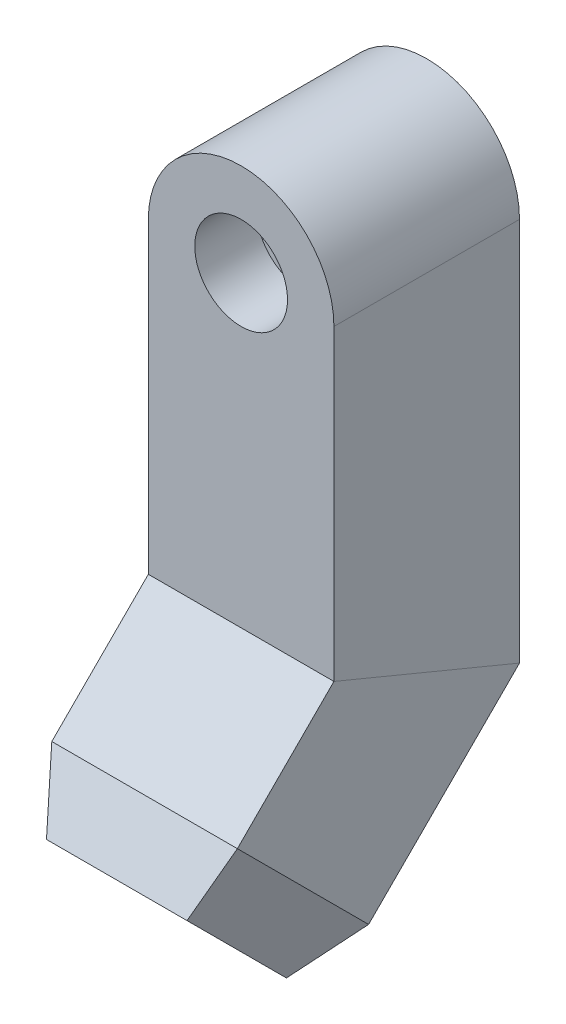
SolidWorks part; units mm, degrees
ref_plane "Front Plane" through (0, 0, 0) normal (0, 0, 1) x (1, 0, 0)
ref_plane "Top Plane" through (0, 0, 0) normal (0, 1, 0) x (1, 0, 0)
ref_plane "Right Plane" through (0, 0, 0) normal (1, 0, 0) x (0, 0, -1)
ref_plane "Plane2" through (0, 96.393, 0) normal (0, 1, 0) x (1, 0, 0)
sketch "Sketch10" plane through (0, 0, 0) normal (1, 0, 0) x (0, 0, -1)
  line L0 (0, 96.393) -> (0, 25.4)
  line L1 (55, 96.393) -> (-55, 96.393) construction
  line L2 (0, 25.4) -> (-25.4, 0)
  line L3 (55, 0) -> (-55, 0) construction
  dimension "D1" = 70.993
  dimension "D2" = 135
sketch "Sketch11" plane through (0, 96.393, 0) normal (0, 1, 0) x (1, 0, 0)
  line L1 (-19.05, -19.05) -> (19.05, -19.05)
  line L2 (-19.05, -19.05) -> (-19.05, 19.05)
  line L3 (-19.05, 19.05) -> (19.05, 19.05)
  line L4 (19.05, -19.05) -> (19.05, 19.05)
  line L5 (-19.05, -19.05) -> (19.05, 19.05) construction
  line L6 (-19.05, 19.05) -> (19.05, -19.05) construction
  point P0 (0, 0)
  dimension "D1" = 38.1
sweep "Sweep1" add profiles "Sketch11" path "Sketch10"
sketch "Sketch12" plane through (0, -12.7, 12.7) normal (0, -0.7071, 0.7071) x (1, 0, 0)
  line L8 (19.05, -1.0895) -> (19.05, 37.0105)
  line L9 (19.05, 37.0105) -> (-19.05, 37.0105)
  line L10 (-19.05, 37.0105) -> (-19.05, -1.0895)
  line L11 (-19.05, -1.0895) -> (19.05, -1.0895)
  line L12 (19.05, -1.0895) -> (19.05, 37.0105)
  line L13 (19.05, 37.0105) -> (-19.05, 37.0105)
  line L14 (-19.05, 37.0105) -> (-19.05, -1.0895)
  line L15 (-19.05, -1.0895) -> (19.05, -1.0895)
  dimension "D1" = 0
extrude "Boss-Extrude5" add sketch "Sketch12" along normal blind 12.7 draft 20
sketch "Sketch13" plane through (0, 0, -19.05) normal (0, 0, -1) x (-1, 0, 0)
  line L0 (20.955, 96.393) -> (-20.955, 96.393) construction
  line L1 (0, 34.9977) -> (0, -34.9977) construction
  line L2 (-19.05, 96.393) -> (19.05, 96.393)
  arc A0 (19.05, 96.393) -> (-19.05, 96.393) centre (0, 96.393) ccw
  dimension "D1" = 38.1
extrude "Boss-Extrude6" add sketch "Sketch13" against normal up to surface (38.1 mm away) up to face at (0, 64.8419, 19.05)
sketch "Sketch14" plane through (0, 0, 19.05) normal (0, 0, 1) x (1, 0, 0)
  circle A0 centre (0, 96.393) radius 9.525
  arc A1 (19.05, 96.393) -> (-19.05, 96.393) centre (0, 96.393) ccw construction
  dimension "D1" = 19.05
extrude "Cut-Extrude2" cut sketch "Sketch14" against normal blind 12.7
sketch "Sketch15" plane through (0, -21.6803, 21.6803) normal (0, -0.7071, 0.7071) x (1, 0, 0)
  line L0 (0, -34.9977) -> (0, 34.9977) construction
  line L4 (-14.4276, 32.3881) -> (-14.4276, 3.5329) construction
  line L5 (-14.4276, 3.5329) -> (14.4276, 3.5329) construction
  line L8 (0, 32.3881) -> (0, 3.5329) construction
  line L9 (14.4276, 32.3881) -> (-14.4276, 32.3881) construction
  circle A0 centre (0, 17.9605) radius 9.525
  point P12 (-14.4276, 17.9605)
  dimension "D1" = 19.05
extrude "Cut-Extrude3" cut sketch "Sketch15" against normal blind 12.7
